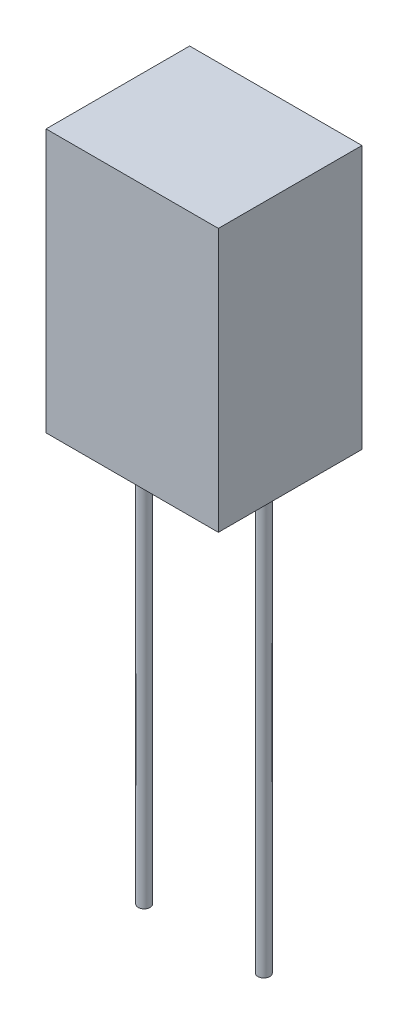
SolidWorks part; units mm, degrees
ref_plane "Front Plane" through (0, 0, 0) normal (0, 0, 1) x (1, 0, 0)
ref_plane "Top Plane" through (0, 0, 0) normal (0, 1, 0) x (1, 0, 0)
ref_plane "Right Plane" through (0, 0, 0) normal (1, 0, 0) x (0, 0, -1)
sketch "Sketch1" plane through (0, 0, 0) normal (0, 0, 1) x (1, 0, 0)
  line L1 (-3.6, 5.5) -> (3.6, 5.5)
  line L2 (-3.6, 5.5) -> (-3.6, -5.5)
  line L3 (-3.6, -5.5) -> (3.6, -5.5)
  line L4 (3.6, 5.5) -> (3.6, -5.5)
  line L5 (-3.6, 5.5) -> (3.6, -5.5) construction
  line L6 (-3.6, -5.5) -> (3.6, 5.5) construction
  point P0 (0, 0)
  dimension "D1" = 7.2
  dimension "D2" = 11
extrude "Boss-Extrude1" add sketch "Sketch1" along normal blind 6
sketch "Sketch2" plane through (0, -5.5, 0) normal (0, -1, 0) x (1, 0, 0)
  line L0 (-2.5, 3) -> (2.5, 3) construction
  line L1 (0, 0) -> (0, 3) construction
  line L2 (0, 3) -> (0, 6) construction
  line L3 (-3.6, 6) -> (3.6, 6) construction
  circle A0 centre (-2.5, 3) radius 0.25
  circle A1 centre (2.5, 3) radius 0.25
  point P3 (0, 3)
  dimension "D2" = 0.5
  dimension "D1" = 5
extrude "Boss-Extrude2" add sketch "Sketch2" along normal blind 18
